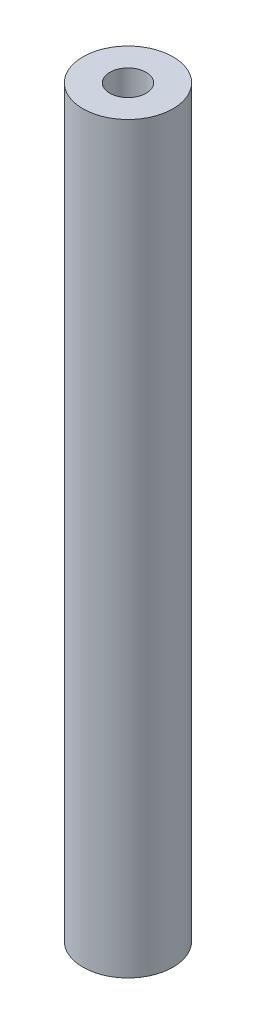
SolidWorks part; units mm, degrees
material "AISI 316 Annealed Stainless Steel Bar (SS)"
ref_plane "Front Plane" through (0, 0, 0) normal (0, 0, 1) x (1, 0, 0)
ref_plane "Top Plane" through (0, 0, 0) normal (0, 1, 0) x (1, 0, 0)
ref_plane "Right Plane" through (0, 0, 0) normal (1, 0, 0) x (0, 0, -1)
sketch "Sketch1" plane through (0, 0, 0) normal (0, 1, 0) x (1, 0, 0)
  circle A0 centre (0, 0) radius 5
  dimension "D1" = 10
extrude "Boss-Extrude2" add sketch "Sketch1" against normal blind 82.55
ref_plane "Plane1" through (0, 0, -5) normal (0, 0, -1) x (-1, 0, 0)
sketch "Sketch2" plane through (0, 0, -5) normal (0, 0, -1) x (-1, 0, 0)
  line L0 (0, -10.39) -> (0, -15.39) construction
  line L1 (0, -82.55) -> (0, 0) construction
  line L2 (1.5, -10.39) -> (1.5, -15.39)
  line L3 (-1.5, -10.39) -> (-1.5, -15.39)
  line L5 (0, -63.5) -> (0, -68.5) construction
  line L6 (1.5, -63.5) -> (1.5, -68.5)
  line L7 (-1.5, -63.5) -> (-1.5, -68.5)
  line L8 (5, 0) -> (-5, 0) construction
  line L9 (0, -109.22) -> (0, -114.22) construction
  line L10 (2, -109.22) -> (2, -114.22)
  line L11 (-2, -109.22) -> (-2, -114.22)
  arc A0 (1.5, -10.39) -> (-1.5, -10.39) centre (0, -10.39) ccw
  arc A1 (-1.5, -15.39) -> (1.5, -15.39) centre (0, -15.39) ccw
  arc A2 (1.5, -63.5) -> (-1.5, -63.5) centre (0, -63.5) ccw
  arc A3 (-1.5, -68.5) -> (1.5, -68.5) centre (0, -68.5) ccw
  arc A4 (2, -109.22) -> (-2, -109.22) centre (0, -109.22) ccw
  arc A5 (-2, -114.22) -> (2, -114.22) centre (0, -114.22) ccw
  point P5 (0, -12.89)
  point P10 (0, -8.89)
  point P11 (0, -16.89)
  point P14 (0, -66)
  point P19 (0, -111.72)
  dimension "D2" = 8
  dimension "D5" = 109.22
  dimension "D1" = 3
  dimension "D3" = 8.89
  dimension "D4" = 63.5
  dimension "D6" = 4
extrude "Cut-Extrude1" cut sketch "Sketch2" against normal blind 2.54 contours L11 A5 L10 A4 | L7 A3 L6 A2 | L3 A1 L2 A0
hole_wizard "Tap Drill for #10-32 Tap1" positions "3DSketch1" profile "Sketch3" hole size "#10-32" standard "ANSI Inch"
sketch3d "3DSketch1"
  line L0 (0, -82.55, 0) -> (0, 0, 0) construction
  circle A0 centre (0, 0, 0) radius 5 construction
  point P0 (0, 0, 0)
  point P3 (0, -82.55, 0)
  point P7 (0, 0, 0)
  point P9 (0, 0, 0)
  point P14 (0, 5, 0)
sketch "Sketch3" plane through (0, 0, 0) normal (1, 0, 0) x (0, 0, 1)
  line L0 (0, 0) -> (0, 12.7)
  line L1 (0, 12.7) -> (2.0193, 11.4867)
  line L2 (2.0193, 11.4867) -> (2.0193, 0)
  line L5 (2.0193, 0) -> (0, 0)
  line L10 (0, 12.7) -> (-2.0193, 11.4867) construction
  line L11 (0, -6.35) -> (0, 107.95) construction
  dimension "Hole Dia." = 4.0386
  dimension "Hole Depth" = 12.7
  dimension "Drill Angle" = 118
